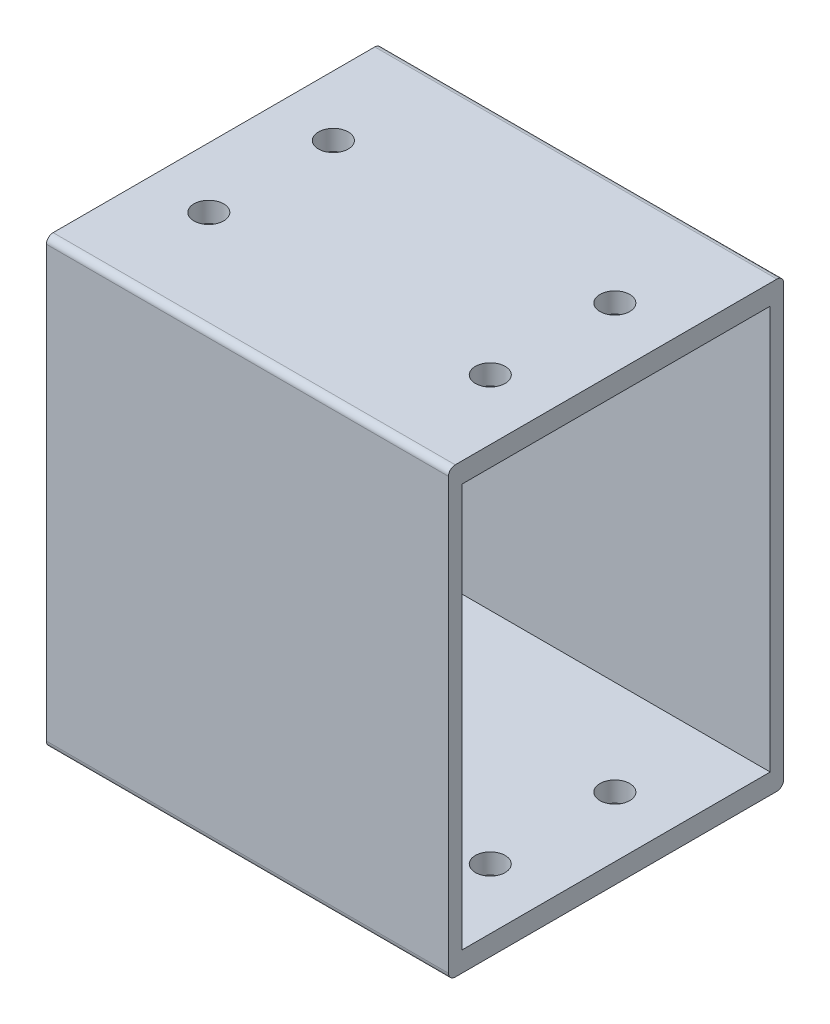
SolidWorks part; units mm, degrees
ref_plane "Front Plane" through (0, 0, 0) normal (0, 0, 1) x (1, 0, 0)
ref_plane "Top Plane" through (0, 0, 0) normal (0, 1, 0) x (1, 0, 0)
ref_plane "Right Plane" through (0, 0, 0) normal (1, 0, 0) x (0, 0, -1)
sketch "Sketch2" plane through (0, 0, 0) normal (1, 0, 0) x (0, 0, -1)
  line L1 (-31.75, -42.037) -> (31.75, -42.037)
  line L2 (-31.75, -42.037) -> (-31.75, 42.037)
  line L3 (-31.75, 42.037) -> (31.75, 42.037)
  line L4 (31.75, -42.037) -> (31.75, 42.037)
  line L5 (-31.75, -42.037) -> (31.75, 42.037) construction
  line L6 (-31.75, 42.037) -> (31.75, -42.037) construction
  point P0 (0, 0)
  dimension "D1" = 84.074
  dimension "D2" = 63.5
extrude "Boss-Extrude1" add sketch "Sketch2" along normal blind 76.2
sketch "Sketch3" plane through (0, 0, 31.75) normal (0, 0, 1) x (1, 0, 0)
  line L12 (76.2, 42.037) -> (0, 42.037) construction
  line L13 (36.195, -42.037) -> (40.005, -42.037)
  line L14 (36.195, -42.037) -> (36.195, 42.037)
  line L15 (36.195, 42.037) -> (40.005, 42.037)
  line L16 (40.005, -42.037) -> (40.005, 42.037)
  line L17 (36.195, -42.037) -> (40.005, 42.037) construction
  line L18 (36.195, 42.037) -> (40.005, -42.037) construction
  point P0 (38.1, 0)
  point P7 (38.1, 42.037)
  point P8 (38.1, 42.037)
  dimension "D1" = 3.81
  dimension "D2" = 36.195
sketch "Sketch6" plane through (0, 0, 0) normal (-1, 0, 0) x (0, 0, 1)
  line L0 (-31.75, 42.037) -> (31.75, 42.037) construction
  line L1 (-29.21, -38.227) -> (29.21, -38.227)
  line L3 (-29.21, 38.227) -> (29.21, 38.227)
  line L4 (29.21, -38.227) -> (29.21, 38.227)
  line L5 (-29.21, 38.227) -> (-29.21, -38.227)
  line L7 (31.75, 42.037) -> (31.75, -42.037) construction
  line L8 (-31.75, -42.037) -> (-31.75, 42.037) construction
  point P0 (0, 0)
  point P10 (29.21, 0)
  dimension "D1" = 3.81
  dimension "D2" = 2.54
  dimension "D3" = 2.54
extrude "Cut-Extrude1" cut sketch "Sketch6" against normal up to next
extrude "Boss-Extrude4" [suppressed] add sketch "Sketch3" along normal blind 5.08
sketch "Sketch8" [suppressed] plane through (0, 42.037, 0) normal (0, 1, 0) x (1, 0, 0)
  line L0 (76.2, 34.925) -> (0, 34.925) construction
  line L2 (36.195, -40.005) -> (36.195, 34.925)
  line L3 (36.195, 34.925) -> (40.005, 34.925)
  line L4 (40.005, -40.005) -> (40.005, 34.925)
  line L5 (36.195, -40.005) -> (40.005, -40.005)
extrude "Boss-Extrude5" [suppressed] add sketch "Sketch8" along normal blind 5.08
fillet "Fillet1" radius 1.27 4 edges at (38.1, -42.037, -31.75) (38.1, 42.037, -31.75) (38.1, -42.037, 31.75) (38.1, 42.037, 31.75)
sketch "Sketch7" plane through (0, -42.037, 0) normal (0, -1, 0) x (1, 0, 0)
  line L5 (0, 30.48) -> (0, -30.48) construction
  line L6 (76.2, 30.48) -> (76.2, -30.48) construction
  line L7 (76.2, -31.75) -> (0, -31.75) construction
  circle A0 centre (11.43, 12.4079) radius 2.8194
  circle A1 centre (64.77, 12.4079) radius 2.8194
  circle A2 centre (11.43, -11.2014) radius 2.8194
  circle A3 centre (64.77, -11.2014) radius 2.8194
  dimension "D3" = 5.6388
  dimension "D1" = 19.3421
  dimension "D2" = 19.3421
  dimension "D4" = 11.43
  dimension "D5" = 11.43
  dimension "D6" = 20.5486
  dimension "D7" = 20.5486
  dimension "D8" = 11.43
  dimension "D9" = 11.43
extrude "Cut-Extrude3" cut sketch "Sketch7" against normal through all both and the other way through all
